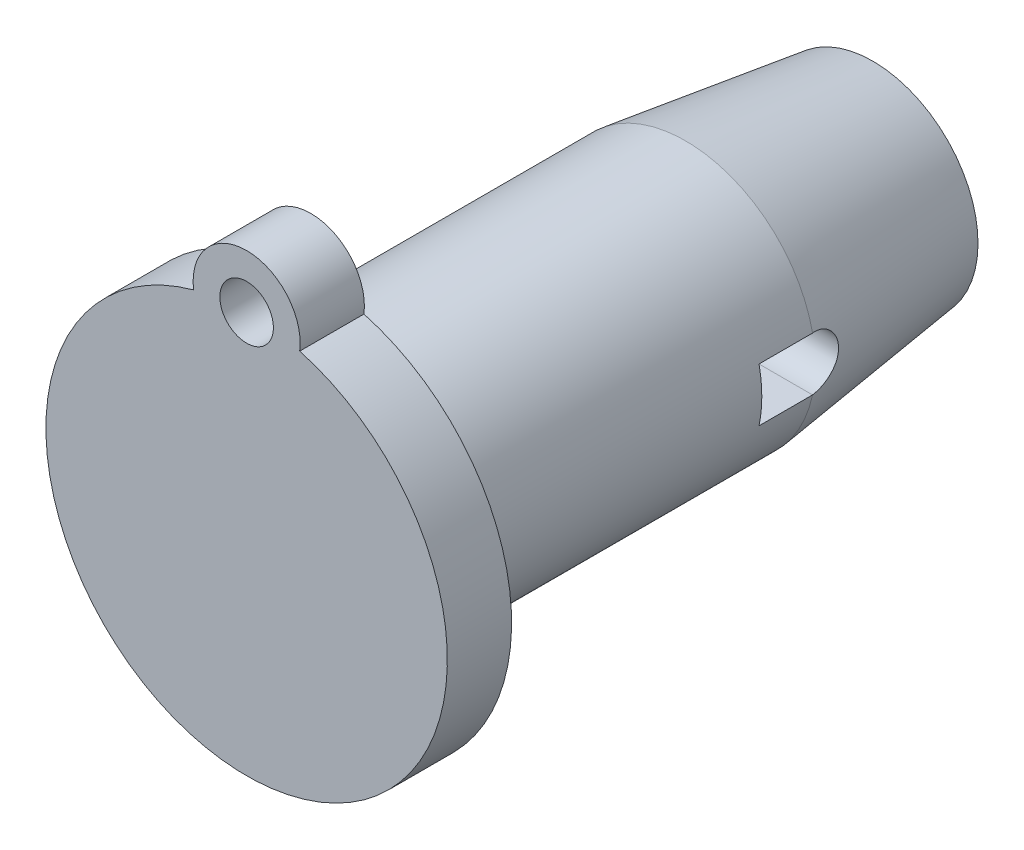
SolidWorks part; units mm, degrees
ref_plane "前视基准面" through (0, 0, 0) normal (0, 0, 1) x (1, 0, 0)
ref_plane "上视基准面" through (0, 0, 0) normal (0, 1, 0) x (1, 0, 0)
ref_plane "右视基准面" through (0, 0, 0) normal (1, 0, 0) x (0, 0, -1)
sketch "草图1" plane through (0, 0, 0) normal (0, 0, 1) x (1, 0, 0)
  circle A0 centre (0, 0) radius 37.5
  dimension "D1" = 75
extrude "拉伸1" add sketch "草图1" along normal blind 12
sketch "草图2" plane through (0, 0, 0) normal (0, 0, -1) x (-1, 0, 0)
  circle A0 centre (0, 0) radius 24.25
  dimension "D1" = 48.5
extrude "拉伸2" add sketch "草图2" along normal blind 105
chamfer "倒角1" distance 35 angle 7.5 1 edges at (-24.25, 0, -105)
ref_plane "基准面1" through (100, 0, 0) normal (1, 0, 0) x (0, 0, -1)
sketch "草图3" plane through (100, 0, 0) normal (1, 0, 0) x (0, 0, -1)
  line L1 (60, 5) -> (70, 5)
  line L2 (60, 5) -> (60, -5)
  line L3 (60, -5) -> (70, -5)
  arc A0 (70, 5) -> (70, -5) centre (70, 0) cw
  dimension "D1" = 10
  dimension "D2" = 10
  dimension "D3" = 60
  dimension "D4" = 5
extrude "拉伸3" cut sketch "草图3" against normal through all
sketch "草图6" plane through (0, 0, 0) normal (0, 0, -1) x (-1, 0, 0)
  circle A0 centre (0, 37.5) radius 10
  circle A2 centre (0, 0) radius 37.5 construction
  dimension "D1" = 20
extrude "拉伸4" add sketch "草图6" against normal blind 12
sketch "草图7" plane through (0, 0, 0) normal (0, 0, -1) x (-1, 0, 0)
  circle A0 centre (0, 37.5) radius 5
  arc A1 (-9.9107, 36.1667) -> (9.9107, 36.1667) centre (0, 0) ccw construction
  dimension "D1" = 10
extrude "拉伸5" cut sketch "草图7" against normal through all
